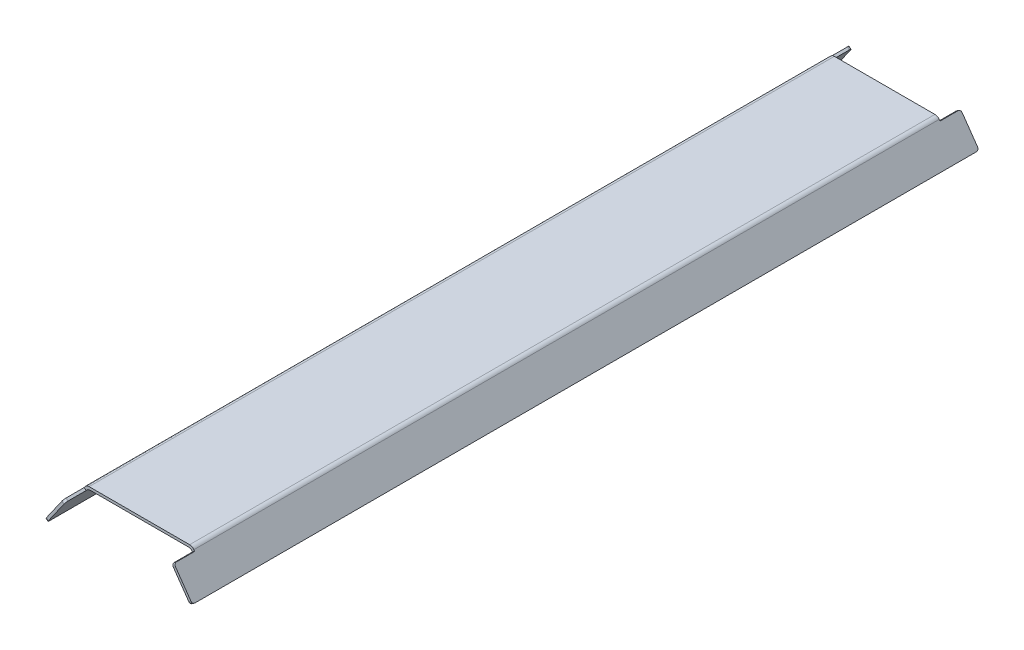
SolidWorks part; units mm, degrees
ref_plane "Front Plane" through (0, 0, 0) normal (0, 0, 1) x (1, 0, 0)
ref_plane "Top Plane" through (0, 0, 0) normal (0, 1, 0) x (1, 0, 0)
ref_plane "Right Plane" through (0, 0, 0) normal (1, 0, 0) x (0, 0, -1)
sketch "Sketch2" plane through (0, 0, 0) normal (0, 0, 1) x (1, 0, 0)
  line L0 (13.8404, -6.0209) -> (10.2733, -0.9264)
  line L1 (9.4541, -0.5) -> (-9.4541, -0.5)
  line L2 (-10.2733, -0.9264) -> (-13.8404, -6.0209)
  line L3 (14.25, -5.7341) -> (10.5335, -0.4264)
  line L4 (9.7144, 0) -> (-9.7144, 0)
  line L5 (-10.5335, -0.4264) -> (-14.25, -5.7341)
  line L6 (-13.8404, -6.0209) -> (-14.25, -5.7341)
  line L7 (13.8404, -6.0209) -> (14.25, -5.7341)
  line L8 (13.8404, -6.0209) -> (9.9747, -0.5) construction
  line L9 (9.9747, -0.5) -> (-9.9747, -0.5) construction
  line L10 (14.25, -5.7341) -> (10.235, 0) construction
  line L11 (10.235, 0) -> (-10.235, 0) construction
  line L12 (-9.9747, -0.5) -> (-13.8404, -6.0209) construction
  line L13 (-10.235, 0) -> (-14.25, -5.7341) construction
  arc A0 (10.2733, -0.9264) -> (9.4541, -0.5) centre (9.4541, -1.5) ccw
  arc A1 (10.5335, -0.4264) -> (9.7144, 0) centre (9.7144, -1) ccw
  arc A2 (-10.2733, -0.9264) -> (-9.4541, -0.5) centre (-9.4541, -1.5) cw
  arc A3 (-9.7144, 0) -> (-10.5335, -0.4264) centre (-9.7144, -1) ccw
  point P13 (10.235, 0)
  dimension "D4" = 125
  dimension "D6" = 1
  dimension "D1" = 28.5
  dimension "D2" = 7
  dimension "D3" = 125
  dimension "D5" = 0.5
extrude "Boss-Extrude1" add sketch "Sketch2" along normal mid plane 144 contours L5 L6 L2 A2 L1 A0 L0 L7 L3 A1 L4 A3
ref_plane "Plane2" through (6.663, 4.6655, 0) normal (0.8192, 0.5736, 0) x (0, 0, -1)
sketch "Sketch3" plane through (6.663, 4.6655, 0) normal (0.8192, 0.5736, 0) x (0, 0, -1)
  line L0 (-72, -6.6514) -> (-75.5, -6.6514)
  line L1 (-76, -7.1514) -> (-76, -12.3705)
  line L2 (-75.5, -12.8705) -> (-72, -12.8705)
  line L3 (-72, -12.8705) -> (-72, -6.6514)
  line L4 (0, 0) -> (0, -12.8705) construction
  line L5 (-72, -12.8705) -> (72, -12.8705) construction
  line L6 (72, -12.8705) -> (72, -6.6514)
  line L7 (75.5, -12.8705) -> (72, -12.8705)
  line L8 (76, -7.1514) -> (76, -12.3705)
  line L9 (72, -6.6514) -> (75.5, -6.6514)
  arc A0 (75.5, -12.8705) -> (76, -12.3705) centre (75.5, -12.3705) ccw
  arc A1 (76, -7.1514) -> (75.5, -6.6514) centre (75.5, -7.1514) ccw
  arc A2 (-75.5, -12.8705) -> (-76, -12.3705) centre (-75.5, -12.3705) cw
  arc A3 (-76, -7.1514) -> (-75.5, -6.6514) centre (-75.5, -7.1514) cw
  point P18 (76, -12.8705)
  point P21 (76, -6.6514)
  point P24 (-76, -12.8705)
  point P27 (-76, -6.6514)
  dimension "D2" = 0.5
  dimension "D1" = 4
extrude "Boss-Extrude2" add sketch "Sketch3" along normal mid plane 0.5 contours L3 L0 A3 L1 A2 L2 | L8 A0 L7 L6 L9 A1
ref_plane "Plane3" through (-6.663, 4.6655, 0) normal (-0.8192, 0.5736, 0) x (0, 0, 1)
sketch "Sketch4" plane through (-6.663, 4.6655, 0) normal (-0.8192, 0.5736, 0) x (0, 0, 1)
  line L0 (-72, -6.6514) -> (-75.5, -6.6514)
  line L1 (-76, -7.1514) -> (-76, -12.3705)
  line L2 (-75.5, -12.8705) -> (-72, -12.8705)
  line L3 (-72, -12.8705) -> (-72, -6.6514)
  line L4 (0, 0) -> (0, -12.8705) construction
  line L5 (72, -12.8705) -> (-72, -12.8705) construction
  line L6 (72, -12.8705) -> (72, -6.6514)
  line L7 (75.5, -12.8705) -> (72, -12.8705)
  line L8 (76, -7.1514) -> (76, -12.3705)
  line L9 (72, -6.6514) -> (75.5, -6.6514)
  arc A0 (-75.5, -12.8705) -> (-76, -12.3705) centre (-75.5, -12.3705) cw
  arc A1 (-75.5, -6.6514) -> (-76, -7.1514) centre (-75.5, -7.1514) ccw
  arc A2 (75.5, -12.8705) -> (76, -12.3705) centre (75.5, -12.3705) ccw
  arc A3 (76, -7.1514) -> (75.5, -6.6514) centre (75.5, -7.1514) ccw
  point P17 (-76, -12.8705)
  point P20 (-76, -6.6514)
  point P23 (76, -12.8705)
  point P26 (76, -6.6514)
  dimension "D2" = 0.5
  dimension "D3" = 0.5
  dimension "D1" = 4
extrude "Boss-Extrude3" add sketch "Sketch4" along normal mid plane 0.5
